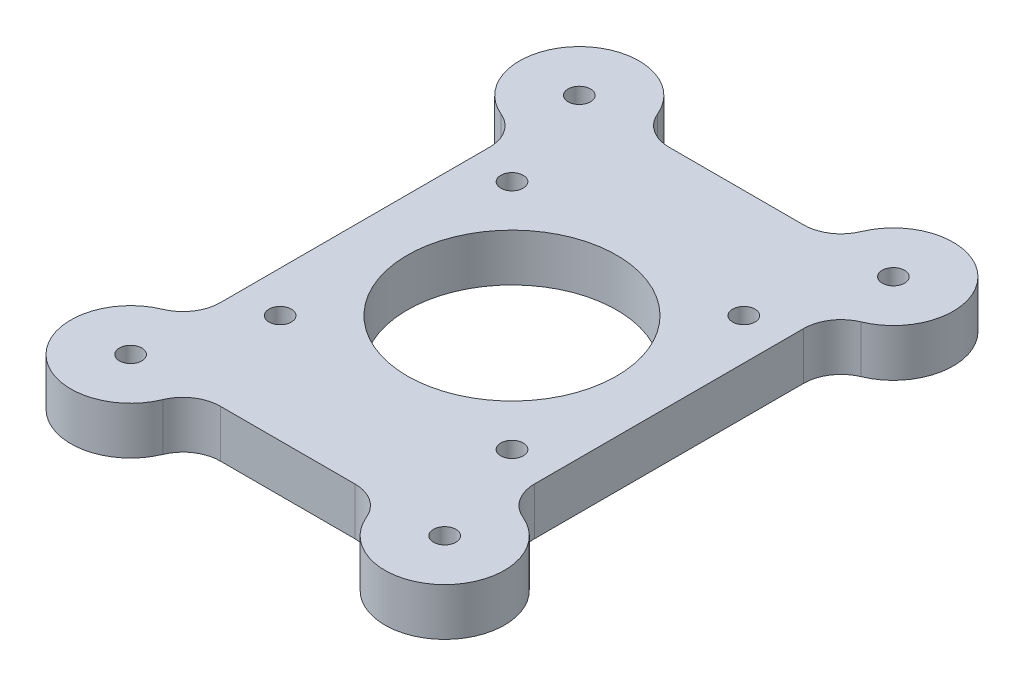
SolidWorks part; units mm, degrees
ref_plane "Front Plane" through (0, 0, 0) normal (0, 0, 1) x (1, 0, 0)
ref_plane "Top Plane" through (0, 0, 0) normal (0, 1, 0) x (1, 0, 0)
ref_plane "Right Plane" through (0, 0, 0) normal (1, 0, 0) x (0, 0, -1)
sketch "Sketch1" plane through (0, 0, 0) normal (0, 1, 0) x (1, 0, 0)
  line L0 (-21, -30) -> (21, -30) construction
  line L1 (21, -30) -> (-21, -30)
  line L2 (21, -30) -> (21, 30)
  line L3 (21, 30) -> (-21, 30)
  line L4 (-21, -30) -> (-21, 30)
  line L5 (21, -30) -> (-21, 30) construction
  line L6 (21, 30) -> (-21, -30) construction
  line L7 (21, -30) -> (21, 30) construction
  line L8 (21, 30) -> (-21, 30) construction
  line L9 (-21, 30) -> (-21, -30) construction
  circle A0 centre (-21, 30) radius 8
  circle A1 centre (21, 30) radius 8
  circle A2 centre (-21, -30) radius 8
  circle A3 centre (21, -30) radius 8
  point P0 (0, 0)
  point P14 (-11.8363, -23.6726)
  point P15 (-14.7838, 29.5676)
  point P16 (-21, 41.105)
  dimension "D3" = 16
  dimension "D1" = 60
  dimension "D2" = 42
extrude "Boss-Extrude1" add sketch "Sketch1" along normal blind 6.35 contours L4 A2 L1 | L1 A2 L4 | L1 A3 L2 | L2 A3 L1 | A3 L2 A1 L3 A0 L4 A2 L1 | L2 A1 L3 | L3 A1 L2 | L4 A0 L3 | L3 A0 L4
sketch "Sketch2" plane through (0, 6.35, 0) normal (0, 1, 0) x (1, 0, 0)
  line L0 (-15.5, 15.5) -> (15.5, 15.5) construction
  line L1 (15.5, 15.5) -> (15.5, -15.5) construction
  line L2 (15.5, -15.5) -> (-15.5, -15.5) construction
  line L3 (-15.5, -15.5) -> (-15.5, 15.5) construction
  circle A0 centre (-15.5, -15.5) radius 1.5
  circle A1 centre (15.5, -15.5) radius 1.5
  circle A2 centre (15.5, 15.5) radius 1.5
  circle A3 centre (-15.5, 15.5) radius 1.5
  circle A4 centre (0, 0) radius 14
  point P10 (0, 0)
  point P12 (15.5, 20.7934)
  point P13 (0, 15.5)
  dimension "D1" = 3
  dimension "D2" = 28
  dimension "D3" = 15.5
  dimension "D4" = 15.5
extrude "Cut-Extrude1" cut sketch "Sketch2" against normal through all
sketch "Sketch3" plane through (0, 6.35, 0) normal (0, 1, 0) x (1, 0, 0)
  circle A0 centre (-21, 30) radius 1.5
  circle A1 centre (21, 30) radius 1.5
  circle A2 centre (21, -30) radius 1.5
  circle A3 centre (-21, -30) radius 1.5
  dimension "D1" = 3
extrude "Cut-Extrude2" cut sketch "Sketch3" against normal through all
fillet "Fillet1" radius 5 8 edges at (21, 3.175, 22) (21, 3.175, -22) (-13, 3.175, -30) (13, 3.175, -30) (-21, 3.175, -22) (-21, 3.175, 22) (13, 3.175, 30) (-13, 3.175, 30)
